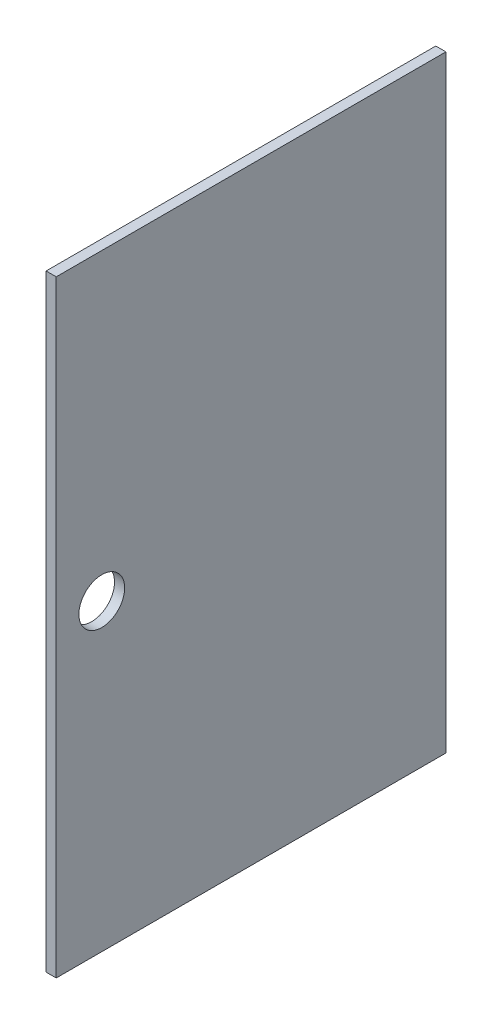
SolidWorks part; units mm, degrees
ref_plane "Front Plane" through (0, 0, 0) normal (0, 0, 1) x (1, 0, 0)
ref_plane "Top Plane" through (0, 0, 0) normal (0, 1, 0) x (1, 0, 0)
ref_plane "Right Plane" through (0, 0, 0) normal (1, 0, 0) x (0, 0, -1)
sketch "Sketch1" plane through (0, 0, 0) normal (1, 0, 0) x (0, 0, -1)
  line L1 (122.2375, 190.5) -> (-122.2375, 190.5)
  line L2 (122.2375, 190.5) -> (122.2375, -190.5)
  line L3 (122.2375, -190.5) -> (-122.2375, -190.5)
  line L4 (-122.2375, 190.5) -> (-122.2375, -190.5)
  line L5 (122.2375, 190.5) -> (-122.2375, -190.5) construction
  line L6 (122.2375, -190.5) -> (-122.2375, 190.5) construction
  circle A0 centre (-93.6625, 0) radius 14.351
  point P0 (0, 0)
  dimension "D3" = 28.702
  dimension "D4" = 215.9
  dimension "D1" = 28.575
  dimension "D2" = 381
  dimension "D5" = 190.5
extrude "Boss-Extrude1" add sketch "Sketch1" along normal blind 6.35
